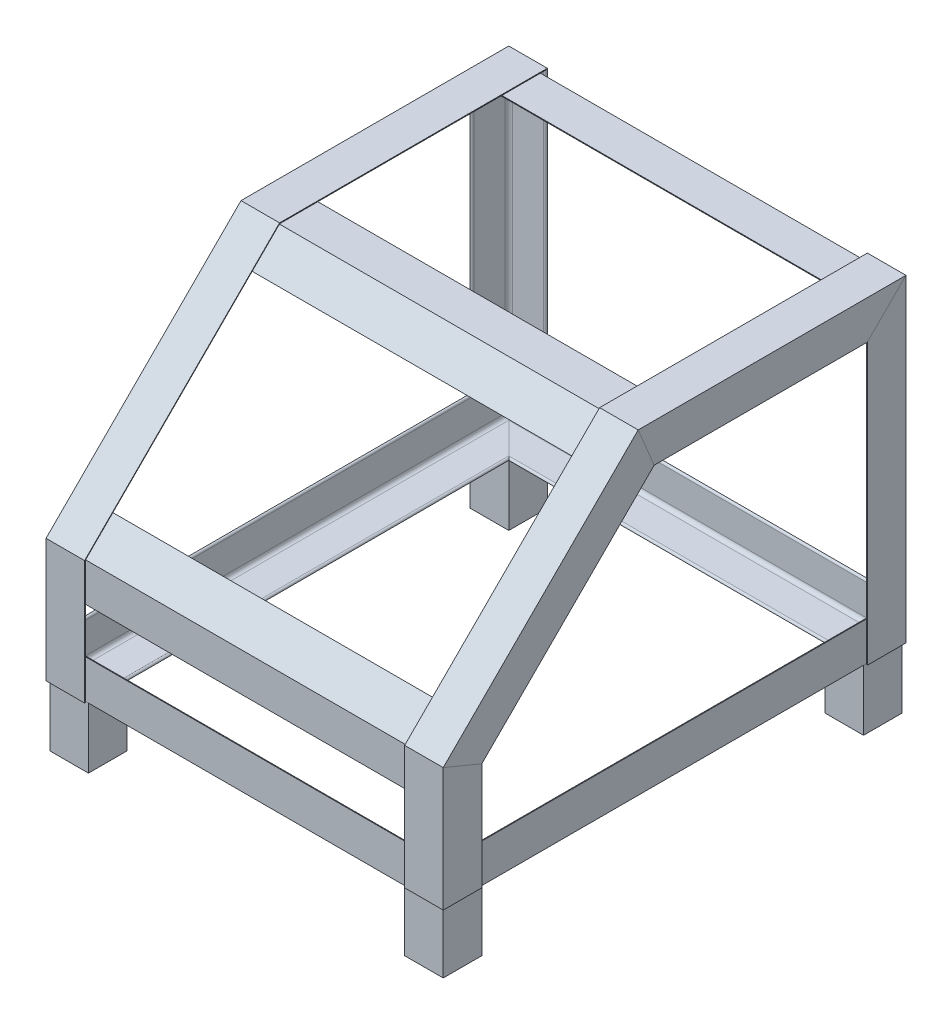
SolidWorks part; units mm, degrees
ref_plane "Front Plane" through (0, 0, 0) normal (0, 0, 1) x (1, 0, 0)
ref_plane "Top Plane" through (0, 0, 0) normal (0, 1, 0) x (1, 0, 0)
ref_plane "Right Plane" through (0, 0, 0) normal (1, 0, 0) x (0, 0, -1)
sketch3d "3DSketch1"
  line L0 (0, 0, 0) -> (0, 438.15, 0)
  line L1 (0, 438.15, 0) -> (641.35, 438.15, 0)
  line L2 (641.35, 438.15, 0) -> (641.35, 0, 0)
  line L3 (641.35, 0, 0) -> (0, 0, 0)
  line L4 (641.35, 0, 0) -> (641.35, 0, -749.3)
  line L5 (641.35, 0, -749.3) -> (0, 0, -749.3)
  line L6 (0, 0, -749.3) -> (0, 0, 0)
  line L7 (641.35, 0, -749.3) -> (641.35, 438.15, -749.3)
  line L8 (641.35, 438.15, -749.3) -> (641.35, 438.15, 0)
  line L9 (0, 438.15, 0) -> (0, 438.15, -749.3)
  line L10 (0, 438.15, -749.3) -> (0, 0, -749.3)
  line L11 (641.35, 438.15, -749.3) -> (0, 438.15, -749.3)
  dimension "D1" = 438.15
  dimension "D2" = 641.35
  dimension "D3" = 749.3
other "Ángulo de extremos redondeados al i AL L ANGLE RND END 2.5X2.5X0.125(1)"
ref_plane "Plane2" through (-3.175, -9.525, -749.3) normal (0, 0, 1) x (1, 0, 0)
sketch "Sketch1" plane through (-3.175, -9.525, -749.3) normal (0, 0, 1) x (1, 0, 0)
  line L0 (0, 0) -> (0, 63.5)
  line L1 (0, 63.5) -> (0.0051, 63.5)
  line L2 (3.175, 60.3301) -> (3.175, 9.525)
  line L3 (9.525, 3.175) -> (60.3301, 3.175)
  line L4 (63.5, 0.0051) -> (63.5, 0)
  line L5 (63.5, 0) -> (0, 0)
  arc A0 (63.5, 0.0051) -> (60.3301, 3.175) centre (60.3301, 0.0051) ccw
  arc A1 (0.0051, 63.5) -> (3.175, 60.3301) centre (0.0051, 60.3301) cw
  arc A2 (9.525, 3.175) -> (3.175, 9.525) centre (9.525, 9.525) cw
  circle A3 centre (0, 0) radius 3.175 construction
  point P10 (0, 31.75)
  point P14 (31.75, 0)
  point P15 (0, 0)
  dimension "D2" = 0.0051
  dimension "Radius_1" = 6.35
  dimension "Radius_2" = 3.175
  dimension "D1" = 3.175
  dimension "V_leg" = 63.5
  dimension "H_leg" = 63.5
  dimension "Thickness" = 3.175
  dimension "Flat_wid" = 0.0051
ref_plane "Plano2" through (320.675, 0, 0) normal (1, 0, 0) x (0, 0, -1)
sketch3d "Croquis3D1"
  line L10 (644.5199, 53.975, -374.65) -> (-3.1699, 53.975, -374.65) construction
  line L11 (644.5199, 53.975, -752.4699) -> (644.5199, 53.975, 3.1699) construction
  line L12 (-3.1699, 53.975, 3.1699) -> (-3.1699, 53.975, -752.4699) construction
  line L13 (320.675, 53.975, -374.65) -> (320.675, 53.975, -752.4699) construction
  line L14 (-3.1699, 53.975, -752.4699) -> (644.5199, 53.975, -752.4699) construction
  line L18 (644.525, -9.525, -752.475) -> (644.525, -9.525, 3.175) construction
  line L19 (644.525, -9.525, -752.475) -> (644.525, -9.525, -755.65) construction
  line L20 (644.525, -9.525, -752.475) -> (647.7, -9.525, -752.475) construction
  line L21 (647.7, -9.525, -752.475) -> (647.7, -9.525, -755.65) construction
  line L22 (644.525, -9.525, -755.65) -> (647.7, -9.525, -755.65) construction
  line L23 (647.7, -9.525, -755.65) -> (647.7, -9.525, 6.35) construction
  line L24 (644.525, -9.525, 3.175) -> (644.525, -9.525, 6.35) construction
  line L25 (644.525, -9.525, 3.175) -> (647.7, -9.525, 3.175) construction
  line L26 (647.7, -9.525, 3.175) -> (647.7, -9.525, 6.35) construction
  line L27 (644.525, -9.525, 6.35) -> (647.7, -9.525, 6.35) construction
  line L28 (647.7, -9.525, 6.35) -> (647.7, 193.675, 6.35)
  line L29 (647.7, -9.525, -755.65) -> (647.7, 514.731, -755.65)
  line L30 (647.7, 193.675, 6.35) -> (647.7, 523.875, 6.35) construction
  line L31 (-6.35, 514.731, -752.475) -> (-6.35, 511.556, -752.475) construction
  line L32 (647.7, 193.675, 6.35) -> (647.7, 514.731, -314.706)
  line L33 (647.7, 514.731, -314.706) -> (647.7, 514.731, -755.65)
  line L34 (647.7, 193.675, 6.35) -> (647.7, 193.675, -755.65) construction
  line L35 (-6.35, -9.525, 6.35) -> (-6.35, 193.675, 6.35)
  line L36 (-6.35, 193.675, 6.35) -> (-6.35, 514.731, -314.706)
  line L37 (-6.35, -9.525, -755.65) -> (-6.35, 514.731, -755.65)
  line L38 (-6.35, 514.731, -314.706) -> (-6.35, 514.731, -755.65)
  line L39 (-6.35, 511.556, -752.475) -> (-6.35, 511.556, -755.65) construction
  line L40 (-6.35, 511.556, -752.475) -> (-3.175, 511.556, -752.475) construction
  line L41 (-3.175, 511.556, -752.475) -> (644.525, 511.556, -752.475)
  line L42 (647.7, 514.731, -752.475) -> (647.7, 511.556, -752.475) construction
  line L43 (647.7, 511.556, -752.475) -> (647.7, 511.556, -755.65) construction
  line L44 (647.7, 511.556, -752.475) -> (644.525, 511.556, -752.475) construction
  line L45 (-6.35, 193.675, 6.35) -> (-3.175, 193.675, 6.35) construction
  line L46 (-3.175, 193.675, 6.35) -> (-3.175, 193.675, 3.175) construction
  line L47 (-3.175, 193.675, 3.175) -> (-6.35, 193.675, 3.175) construction
  line L48 (-6.35, 193.675, 3.175) -> (-6.35, 193.675, 6.35) construction
  line L49 (647.7, 193.675, 6.35) -> (644.5047, 193.675, 6.35) construction
  line L50 (644.5047, 193.675, 6.35) -> (644.5047, 193.675, 3.175) construction
  line L51 (644.5047, 193.675, 3.175) -> (647.7, 193.675, 3.175) construction
  line L52 (644.5047, 193.675, 3.175) -> (-3.175, 193.675, 3.175)
  line L53 (-6.35, 514.731, -314.706) -> (-6.35, 511.556, -314.706) construction
  line L54 (-6.35, 511.556, -314.706) -> (-6.35, 511.556, -317.881) construction
  line L55 (-6.35, 511.556, -317.881) -> (-6.35, 514.731, -317.881) construction
  line L56 (-6.35, 511.556, -314.706) -> (644.525, 511.556, -314.706) construction
  line L57 (647.7, 514.731, -314.706) -> (647.7, 511.556, -314.706) construction
  dimension "D1" = 3.175
  dimension "D3" = 3.175
  dimension "D2" = 3.175
  dimension "D4" = 3.175
  dimension "D5" = 203.2
  dimension "D7" = 3.175
  dimension "D6" = 524.256
  dimension "D9" = 3.175
  dimension "D8" = 45
  dimension "D10" = 3.175
  dimension "D11" = 3.175
  dimension "D12" = 3.175
  dimension "D13" = 3.175
  dimension "D14" = 3.175
  dimension "D15" = 3.175
  dimension "D16" = 3.1953
  dimension "D17" = 3.175
  dimension "D18" = 3.175
  dimension "D19" = 3.175
  dimension "D20" = 3.175
  dimension "D21" = 3.175
  dimension "D22" = 440.944
  dimension "D23" = 454.0417
  dimension "D24" = 135
other "Ángulo de extremos redondeados al i AL L ANGLE RND END 2.5X2.5X0.125(3)"
ref_plane "Plano3" through (647.7, -9.525, 6.35) normal (0, -1, 0) x (-1, 0, 0)
sketch "Sketch12" plane through (647.7, -9.525, 6.35) normal (0, -1, 0) x (-1, 0, 0)
  line L0 (0, 0) -> (0, 63.5)
  line L1 (0, 63.5) -> (0.0051, 63.5)
  line L2 (3.175, 60.3301) -> (3.175, 9.525)
  line L3 (9.525, 3.175) -> (60.3301, 3.175)
  line L4 (63.5, 0.0051) -> (63.5, 0)
  line L5 (63.5, 0) -> (0, 0)
  arc A0 (63.5, 0.0051) -> (60.3301, 3.175) centre (60.3301, 0.0051) ccw
  arc A1 (0.0051, 63.5) -> (3.175, 60.3301) centre (0.0051, 60.3301) cw
  arc A2 (9.525, 3.175) -> (3.175, 9.525) centre (9.525, 9.525) cw
  circle A3 centre (0, 0) radius 3.175 construction
  point P10 (0, 31.75)
  point P14 (31.75, 0)
  point P15 (0, 0)
  dimension "D2" = 0.0051
  dimension "Radius_1" = 6.35
  dimension "Radius_2" = 3.175
  dimension "D1" = 3.175
  dimension "V_leg" = 63.5
  dimension "H_leg" = 63.5
  dimension "Thickness" = 3.175
  dimension "Flat_wid" = 0.0051
other "Ángulo de extremos redondeados al i AL L ANGLE RND END 2.5X2.5X0.125(21)"
ref_plane "Plano8" through (-6.35, -9.525, 6.35) normal (0, 1, 0) x (1, 0, 0)
sketch "Sketch17" plane through (-6.35, -9.525, 6.35) normal (0, 1, 0) x (1, 0, 0)
  line L0 (0, 0) -> (0, 63.5)
  line L1 (0, 63.5) -> (0.0051, 63.5)
  line L2 (3.175, 60.3301) -> (3.175, 9.525)
  line L3 (9.525, 3.175) -> (60.3301, 3.175)
  line L4 (63.5, 0.0051) -> (63.5, 0)
  line L5 (63.5, 0) -> (0, 0)
  arc A0 (63.5, 0.0051) -> (60.3301, 3.175) centre (60.3301, 0.0051) ccw
  arc A1 (0.0051, 63.5) -> (3.175, 60.3301) centre (0.0051, 60.3301) cw
  arc A2 (9.525, 3.175) -> (3.175, 9.525) centre (9.525, 9.525) cw
  circle A3 centre (0, 0) radius 3.175 construction
  point P10 (0, 31.75)
  point P14 (31.75, 0)
  point P15 (0, 0)
  dimension "D2" = 0.0051
  dimension "Radius_1" = 6.35
  dimension "Radius_2" = 3.175
  dimension "D1" = 3.175
  dimension "V_leg" = 63.5
  dimension "H_leg" = 63.5
  dimension "Thickness" = 3.175
  dimension "Flat_wid" = 0.0051
sketch "Croquis2" plane through (-3.175, 0, 0) normal (1, 0, 0) x (0, 0, -1)
  line L0 (-3.175, 192.3599) -> (-3.175, 128.8599)
  line L1 (-3.175, 192.3599) -> (-3.175, -9.525) construction
  line L2 (-3.175, 128.8599) -> (1.5875, 128.8599)
  line L3 (1.5875, 128.8599) -> (1.5875, 190.3872)
  line L4 (3.175, 189.7296) -> (-3.175, 192.3599) construction
  line L5 (-3.175, 192.3599) -> (1.5875, 190.3872) construction
  line L6 (45.0939, 233.8936) -> (1.5875, 190.3872)
  line L7 (41.7263, 237.2612) -> (45.0939, 233.8936)
  line L8 (-3.175, 192.3599) -> (41.7263, 237.2612)
  line L9 (316.0211, 511.556) -> (379.5211, 511.556)
  line L10 (752.475, 511.556) -> (316.0211, 511.556) construction
  line L11 (379.5211, 511.556) -> (379.5211, 506.7935)
  line L12 (379.5211, 506.7935) -> (317.9938, 506.7935)
  line L13 (316.0211, 511.556) -> (318.6514, 505.206) construction
  line L14 (317.9938, 506.7935) -> (316.0211, 511.556) construction
  line L15 (316.0211, 511.556) -> (317.9938, 506.7935) construction
  line L16 (274.4874, 463.2871) -> (317.9938, 506.7935)
  line L17 (271.1198, 466.6547) -> (274.4874, 463.2871)
  line L18 (316.0211, 511.556) -> (271.1198, 466.6547)
  dimension "D1" = 4.7625
  dimension "D2" = 63.5
  dimension "D3" = 4.7625
  dimension "D4" = 63.5
extrude "Saliente-Extruir1" add sketch "Croquis2" along normal up to surface (647.7 mm away) separate body up to face at (644.525, 329.5055, -178.8755)
sketch3d "Croquis3D5"
  line L0 (638.175, 511.556, -752.475) -> (644.525, 505.206, -746.125) construction
  line L1 (-3.175, 505.206, -746.125) -> (3.175, 511.556, -752.475) construction
  line L2 (0, 508.381, -749.3) -> (641.35, 508.381, -749.3)
other "Ángulo de extremos redondeados al i AL L ANGLE RND END 2.5X2.5X0.125(26)"
ref_plane "Plano11" through (0, 508.381, -749.3) normal (-1, 0, 0) x (0, -1, 0)
sketch "Sketch110" plane through (0, 508.381, -749.3) normal (-1, 0, 0) x (0, -1, 0)
  line L0 (0, 0) -> (0, 63.5)
  line L1 (0, 63.5) -> (0.0051, 63.5)
  line L2 (3.175, 60.3301) -> (3.175, 9.525)
  line L3 (9.525, 3.175) -> (60.3301, 3.175)
  line L4 (63.5, 0.0051) -> (63.5, 0)
  line L5 (63.5, 0) -> (0, 0)
  arc A0 (63.5, 0.0051) -> (60.3301, 3.175) centre (60.3301, 0.0051) ccw
  arc A1 (0.0051, 63.5) -> (3.175, 60.3301) centre (0.0051, 60.3301) cw
  arc A2 (9.525, 3.175) -> (3.175, 9.525) centre (9.525, 9.525) cw
  circle A3 centre (0, 0) radius 3.175 construction
  point P10 (0, 31.75)
  point P14 (31.75, 0)
  point P15 (0, 0)
  dimension "D2" = 0.0051
  dimension "Radius_1" = 6.35
  dimension "Radius_2" = 3.175
  dimension "D1" = 3.175
  dimension "V_leg" = 63.5
  dimension "H_leg" = 63.5
  dimension "Thickness" = 3.175
  dimension "Flat_wid" = 0.0051
sketch "Croquis4" plane through (647.7, 0, 0) normal (1, 0, 0) x (0, 0, -1)
  line L1 (57.15, 167.3724) -> (-67.4689, 42.7535)
  line L2 (341.0086, 451.231) -> (57.15, 167.3724) construction
  line L3 (-6.35, 193.675) -> (-97.3961, 102.6289)
  line L4 (314.706, 514.731) -> (-6.35, 193.675) construction
  line L5 (38.5513, 148.7737) -> (-6.35, 193.675)
  line L6 (341.0086, 451.231) -> (442.2237, 552.4462)
  line L7 (314.706, 514.731) -> (359.6073, 469.8297)
  line L8 (-6.35, 193.675) -> (83.4526, 193.675)
  line L9 (692.15, 451.231) -> (692.15, 514.731)
  line L10 (755.65, 514.731) -> (314.706, 514.731) construction
  line L11 (692.15, 514.731) -> (755.65, 514.731)
  line L12 (755.65, 514.731) -> (692.15, 451.231)
  dimension "D1" = 63.5
  dimension "D2" = 26.3026
  dimension "D3" = 45
  dimension "D4" = 63.5
sketch3d "Croquis3D6"
  line L1 (28.575, -9.525, -28.575) -> (28.575, -109.525, -28.575)
  line L2 (60.325, -9.525, -60.325) -> (-3.175, -9.525, 3.175) construction
  line L5 (612.775, -9.525, -28.575) -> (612.775, -109.525, -28.575)
  line L6 (581.025, -9.525, -60.325) -> (644.525, -9.525, 3.175) construction
  line L7 (612.775, -9.525, -720.725) -> (612.775, -109.525, -720.725)
  line L8 (644.525, -9.525, -752.475) -> (581.025, -9.525, -688.975) construction
  line L9 (28.575, -9.525, -720.725) -> (28.575, -109.525, -720.725)
  line L10 (-3.175, -9.525, -752.475) -> (60.325, -9.525, -688.975) construction
  dimension "D1" = 100
other "Tubo cuadrado al AL TUBE 2.5 SQR X 0.25 WALL(1)"
ref_plane "Plano12" through (612.775, -9.525, -720.725) normal (0, -1, 0) x (1, 0, 0)
sketch "Sketch113" plane through (612.775, -9.525, -720.725) normal (0, -1, 0) x (1, 0, 0)
  line L0 (-25.4, -25.4) -> (-25.4, 25.4)
  line L1 (25.4, 25.4) -> (-25.4, 25.4)
  line L2 (25.4, 25.4) -> (25.4, -25.4)
  line L3 (-25.4, -25.4) -> (25.4, -25.4)
  line L4 (-31.75, -31.75) -> (31.75, -31.75)
  line L5 (-31.75, -31.75) -> (-31.75, 31.75)
  line L6 (31.75, 31.75) -> (-31.75, 31.75)
  line L7 (31.75, 31.75) -> (31.75, -31.75)
  line L8 (0, -25.4) -> (0, -31.75) construction
  line L9 (0, -25.4) -> (0, 25.4) construction
  line L10 (0, 25.4) -> (0, 31.75) construction
  line L11 (31.75, 0) -> (25.4, 0) construction
  line L12 (25.4, 0) -> (-25.4, 0) construction
  line L13 (-25.4, 0) -> (-31.75, 0) construction
  point P14 (0, 0)
  point P17 (0, 0)
  dimension "Thickness" = 6.35
  dimension "V_leg" = 63.5
  dimension "H_leg" = 63.5
